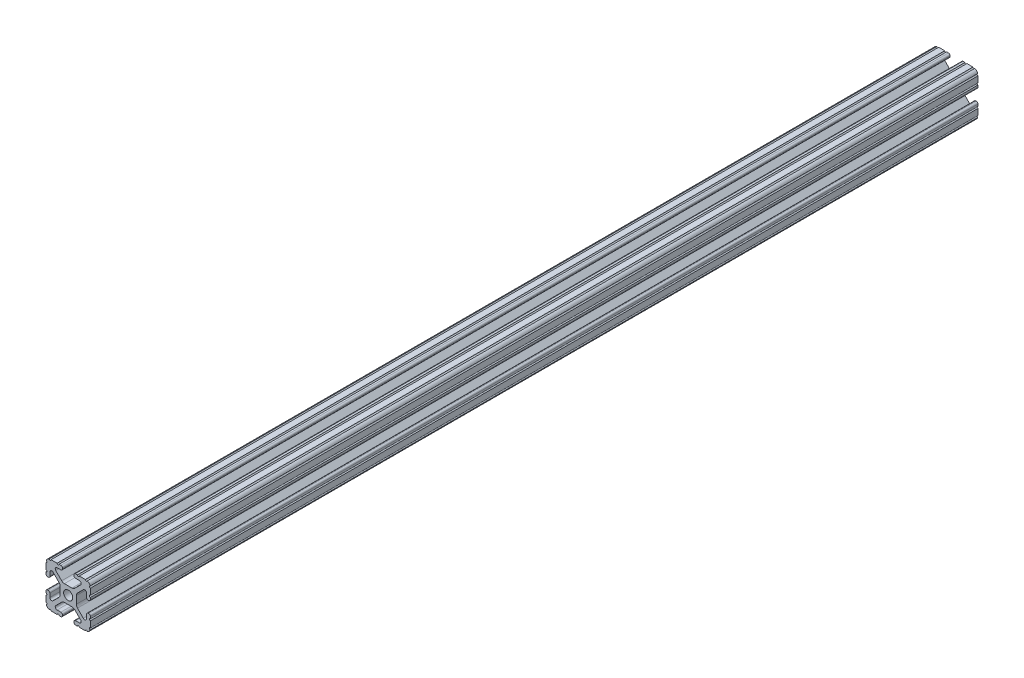
SolidWorks part; units mm, degrees
ref_plane "Front Plane" through (0, 0, 0) normal (0, 0, 1) x (1, 0, 0)
ref_plane "Top Plane" through (0, 0, 0) normal (0, 1, 0) x (1, 0, 0)
ref_plane "Right Plane" through (0, 0, 0) normal (1, 0, 0) x (0, 0, -1)
sketch "Sketch2" plane through (0, 0, 0) normal (0, 0, 1) x (1, 0, 0)
  line L0 (0, 12.7) -> (0, -12.7) construction
  line L1 (-12.7, 0) -> (12.7, 0) construction
  line L2 (3.2512, -12.7) -> (12.7, -12.7)
  line L3 (12.7, -12.7) -> (12.7, -3.2512)
  line L4 (3.2512, -12.7) -> (3.2512, -10.4902)
  line L5 (3.2512, -10.4902) -> (8.9276, -10.4902)
  line L6 (8.9276, -10.4902) -> (3.0856, -4.6482)
  line L7 (0, 0) -> (12.7, -12.7) construction
  line L8 (12.7, -3.2512) -> (10.4902, -3.2512)
  line L9 (10.4902, -3.2512) -> (10.4902, -8.9276)
  line L10 (10.4902, -8.9276) -> (4.6482, -3.0856)
  circle A0 centre (0, 0) radius 2.6035
  arc A1 (6.3485, -10.4902) -> (7.1039, -8.6665) centre (6.3485, -9.4219) ccw construction
  point P8 (0, -4.6482)
  dimension "Center Hole Diameter" = 5.207
  dimension "Rail Height" = 25.4
  dimension "Rail Width" = 25.4
  dimension "T-Slot Width" = 6.5024
  dimension "Slot Inner Width" = 14.8336
  dimension "Thickness" = 2.2098
  dimension "Slot Depth" = 5.842
  dimension "D1" = 2.2098
sketch "Sketch3" plane through (0, 0, 0) normal (1, 0, 0) x (0, 0, -1)
  line L0 (-1524, -12.7) -> (1524, -12.7) construction
  line L1 (-1498.6, 0) -> (1498.6, 0) construction
  dimension "Length" = 3048
  dimension "D1" = 25.4
sketch "Sketch4" plane through (0, 0, 0) normal (0, 0, 1) x (1, 0, 0)
  line L0 (4.1904, -12.7) -> (10.1173, -12.7)
  line L1 (3.2512, -12.7) -> (12.7, -12.7) construction
  line L2 (3.2512, -12.7) -> (3.2512, -10.4902) construction
  line L3 (3.2512, -10.4902) -> (8.9276, -10.4902) construction
  line L4 (3.2512, -11.4294) -> (3.2512, -11.7608)
  line L5 (4.1904, -10.4902) -> (6.3485, -10.4902)
  line L6 (0, -4.6482) -> (2.164, -4.6482)
  line L7 (8.9276, -10.4902) -> (3.0856, -4.6482) construction
  line L8 (3.7373, -5.2999) -> (7.1039, -8.6665)
  line L9 (12.7, -12.7) -> (12.7, -3.2512) construction
  line L10 (10.4902, -8.9276) -> (4.6482, -3.0856) construction
  line L11 (10.4902, -3.2512) -> (10.4902, -8.9276) construction
  line L12 (10.4902, -6.3485) -> (10.4902, -4.1904)
  line L13 (12.7, -3.2512) -> (10.4902, -3.2512) construction
  line L14 (11.4294, -3.2512) -> (11.7608, -3.2512)
  line L15 (12.7, -4.1904) -> (12.7, -10.1173)
  line L16 (8.6665, -7.1039) -> (5.2999, -3.7373)
  line L17 (4.6482, 0) -> (4.6482, -2.164)
  line L18 (-12.7, 0) -> (12.7, 0) construction
  line L19 (0, -4.6482) -> (0, -2.6035)
  line L20 (0, 12.7) -> (0, -12.7) construction
  line L21 (4.6482, 0) -> (2.6035, 0)
  arc A0 (3.2512, -11.7608) -> (4.1904, -12.7) centre (4.1904, -11.7608) ccw
  arc A2 (3.2512, -11.4294) -> (4.1904, -10.4902) centre (4.1904, -11.4294) cw
  arc A3 (6.3485, -10.4902) -> (7.1039, -8.6665) centre (6.3485, -9.4219) ccw
  arc A4 (2.164, -4.6482) -> (3.7373, -5.2999) centre (2.164, -6.8732) cw
  arc A5 (10.1173, -12.7) -> (12.7, -10.1173) centre (10.1173, -10.1173) ccw
  arc A6 (8.6665, -7.1039) -> (10.4902, -6.3485) centre (9.4219, -6.3485) ccw
  arc A7 (10.4902, -4.1904) -> (11.4294, -3.2512) centre (11.4294, -4.1904) cw
  arc A8 (11.7608, -3.2512) -> (12.7, -4.1904) centre (11.7608, -4.1904) cw
  arc A9 (5.2999, -3.7373) -> (4.6482, -2.164) centre (6.8732, -2.164) cw
  circle A10 centre (0, 0) radius 2.6035 construction
  arc A11 (0, -2.6035) -> (2.6035, 0) centre (0, 0) ccw
  dimension "D1" = 2.5827
  dimension "D2" = 2.225
  dimension "D3" = 0.9392
extrude "Boss-Extrude1" add sketch "Sketch4" along normal mid plane 3048
sketch "Sketch5" plane through (0, 0, 0) normal (0, 0, 1) x (1, 0, 0)
  line L0 (3.2512, -12.7) -> (12.7, -12.7) construction
  line L1 (4.1904, -10.4902) -> (6.3485, -10.4902) construction
  line L3 (0, 0) -> (12.7, -12.7) construction
  line L4 (6.3485, -10.4902) -> (6.3485, -12.7) construction
  line L5 (8.9276, -10.4902) -> (3.0856, -4.6482) construction
  circle A0 centre (10.3562, -12.7) radius 0.5524
  circle A1 centre (5.796, -12.7) radius 0.5524
  circle A2 centre (12.7, -10.3562) radius 0.5524
  circle A3 centre (12.7, -5.796) radius 0.5524
  point P10 (5.2694, -10.4902)
  point P12 (9.4219, -6.3485)
  dimension "D1" = 1.1049
extrude "Cut-Extrude1" cut sketch "Sketch5" against normal through all both and the other way through all
mirror "Mirror1" about plane through (0, 0, 0) normal (1, 0, 0) of bodies 137 134
mirror "Mirror2" about plane through (0, 0, 0) normal (0, 1, 0) of bodies 135
sketch "Sketch8" plane through (0, 0, 0) normal (0, 1, 0) x (1, 0, 0)
  line L0 (-12.58, 1524) -> (-12.58, -1524) construction
  line L1 (-25.28, 1536.7) -> (25.28, 1536.7)
  line L2 (-25.28, 1536.7) -> (-25.28, 304.8)
  line L3 (-25.28, 304.8) -> (25.28, 304.8)
  line L4 (25.28, 1536.7) -> (25.28, 304.8)
  line L5 (12.58, 1524) -> (12.58, -1524) construction
  line L6 (-6.3485, 1524) -> (-9.8037, 1524) construction
  dimension "D1" = 12.7
  dimension "D2" = 12.7
  dimension "D3" = 12.7
  dimension "D4" = 1219.2
extrude "Cut-Extrude2" cut sketch "Sketch8" against normal through all both and the other way through all
sketch "Sketch9" plane through (0, 0, 0) normal (0, 1, 0) x (1, 0, 0)
  line L0 (6.3485, -1524) -> (9.8037, -1524) construction
  line L1 (-25.4, 317.5) -> (25.28, 317.5)
  line L2 (-25.4, 317.5) -> (-25.4, -1016)
  line L3 (-25.4, -1016) -> (25.28, -1016)
  line L4 (25.28, 317.5) -> (25.28, -1016)
  line L5 (-9.8037, 304.8) -> (-6.3485, 304.8) construction
  line L7 (-12.7, 304.8) -> (-12.7, -1524) construction
  line L8 (12.58, 304.8) -> (12.58, -1524) construction
  dimension "D1" = 508
  dimension "D2" = 12.7
  dimension "D3" = 12.7
  dimension "D4" = 12.7
extrude "Cut-Extrude3" cut sketch "Sketch9" against normal through all both and the other way through all
equation "\"D1@Boss-Extrude1\"=\"Length@Sketch3\""
equation "\"D1@Sketch2\"=\"Thickness@Sketch2\""
equation "\"D2@Sketch4\"=\"Slot Inner Width@Sketch2\"*0.15"
equation "\"D1@Sketch4\"=\"D3@Sketch4\"*2.75"
equation "\"D3@Sketch4\"=\"Thickness@Sketch2\"*0.425"
equation "\"D1@Sketch5\"=\"Thickness@Sketch2\"*0.5"
